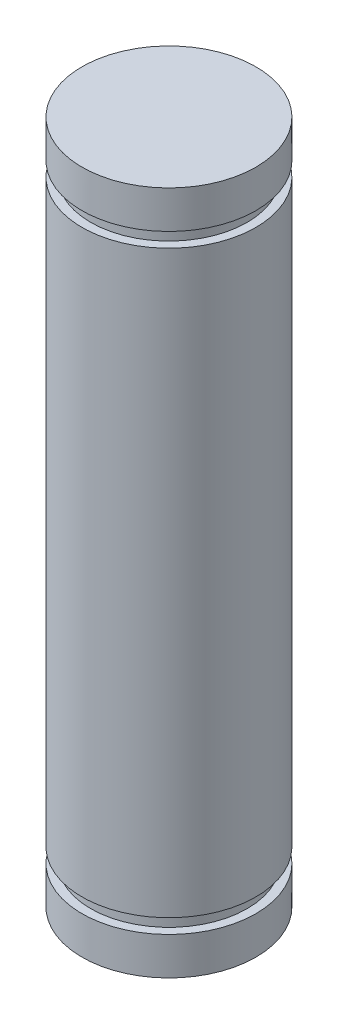
SolidWorks part; units mm, degrees
ref_plane "Plano frontal" through (0, 0, 0) normal (0, 0, 1) x (1, 0, 0)
ref_plane "Plano superior" through (0, 0, 0) normal (0, 1, 0) x (1, 0, 0)
ref_plane "Plano direito" through (0, 0, 0) normal (1, 0, 0) x (0, 0, -1)
sketch "Esboço1" plane through (0, 0, 0) normal (0, 0, 1) x (1, 0, 0)
  line L4 (-3, -11.8) -> (-3, 11.8)
  line L5 (-3, 11.8) -> (0, 11.8)
  line L6 (0, 11.8) -> (0, -11.8)
  line L7 (0, -11.8) -> (-3, -11.8)
  line L8 (0, -11.8) -> (0, 11.8) construction
  dimension "D1" = 3
  dimension "D2" = 23.6
  dimension "D3" = 11.8
revolve "Revolução1" add sketch "Esboço1" angle 360 about L8
sketch "Esboço2" plane through (0, 0, 0) normal (0, 0, 1) x (1, 0, 0)
  line L5 (-2.7, -10) -> (-3, -10)
  line L6 (-3, -11.8) -> (3, -11.8) construction
  line L12 (-2.7, -10.5) -> (-2.7, -10)
  line L14 (-3, -10) -> (-3, -10.5)
  line L15 (-3, -10.5) -> (-2.7, -10.5)
  line L19 (-3, 11.8) -> (-3, -11.8) construction
  line L20 (-2.7, 10) -> (-3, 10)
  line L21 (-3, 10.5) -> (-2.7, 10.5)
  line L22 (-2.7, 10.5) -> (-2.7, 10)
  line L23 (-3, 10) -> (-3, 10.5)
  line L24 (0, 0) -> (0, 11.8) construction
  line L25 (3, 11.8) -> (-3, 11.8) construction
  point P0 (-3, -10)
  point P14 (0, 0)
  point P20 (0, 0)
  dimension "D1" = 0.3
  dimension "D2" = 0.5
  dimension "D3" = 0.3
  dimension "D4" = 0.5
  dimension "D5" = 1.3
  dimension "D6" = 1.3
revolve "Corte-Revolução3" cut sketch "Esboço2" angle 360 about L24
